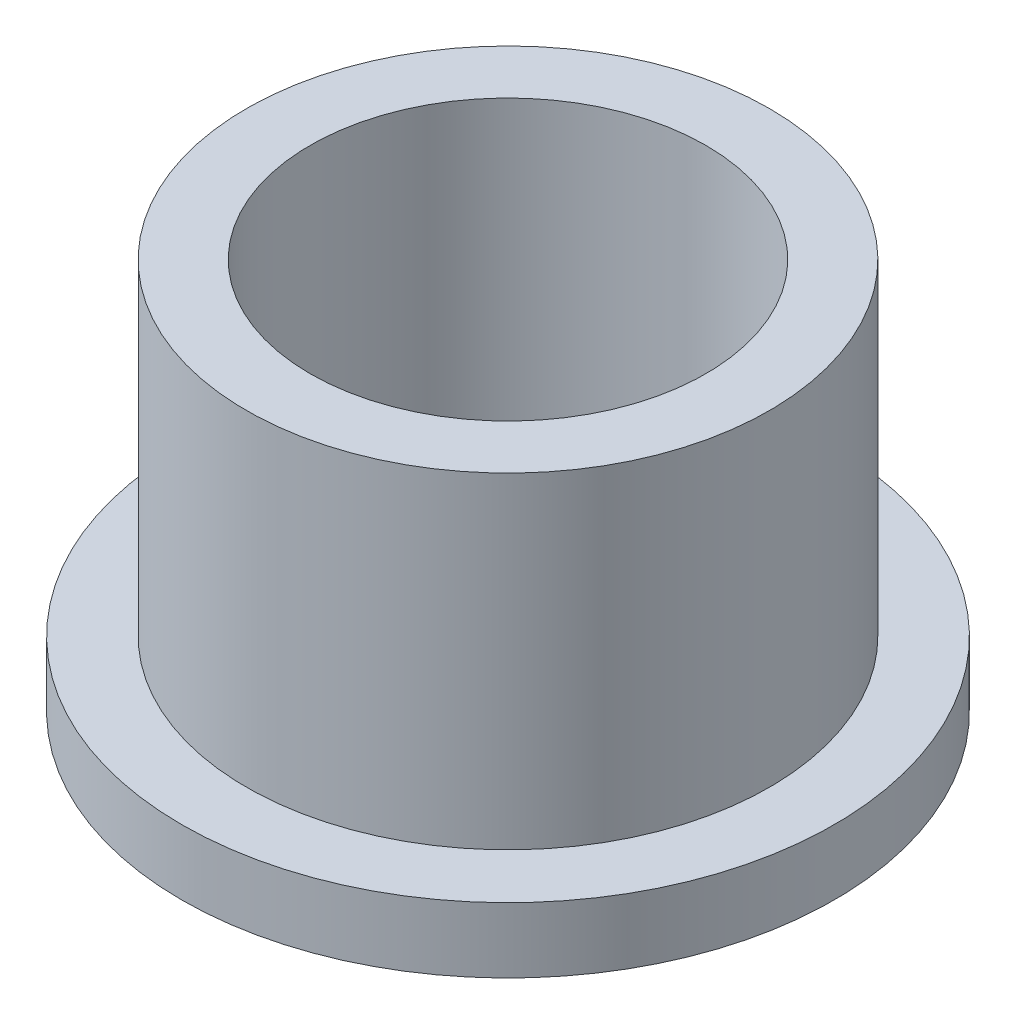
SolidWorks part; units mm, degrees
ref_plane "Front" through (0, 0, 0) normal (0, 0, 1) x (1, 0, 0)
ref_plane "Top" through (0, 0, 0) normal (0, 1, 0) x (1, 0, 0)
ref_plane "Right" through (0, 0, 0) normal (1, 0, 0) x (0, 0, -1)
sketch "Sketch1" plane through (0, 0, 0) normal (0, 1, 0) x (1, 0, 0)
  circle A0 centre (0, 0) radius 4.8133
  circle A1 centre (0, 0) radius 6.3627
  circle A2 centre (0, 0) radius 7.9375
  dimension "ID" = 9.6266
  dimension "OD" = 12.7254
  dimension "FlangeOD" = 15.875
sketch "Sketch2" plane through (0, 0, 0) normal (0, 1, 0) x (1, 0, 0)
  circle A0 centre (0, 0) radius 4.8133 construction
  circle A1 centre (0, 0) radius 6.3627 construction
  circle A2 centre (0, 0) radius 4.8133
  circle A3 centre (0, 0) radius 6.3627
extrude "Boss-Extrude1" add sketch "Sketch2" along normal blind 9.525
sketch "Sketch3" plane through (0, 0, 0) normal (0, 1, 0) x (1, 0, 0)
  circle A0 centre (0, 0) radius 7.9375 construction
  circle A1 centre (0, 0) radius 6.3627 construction
  circle A2 centre (0, 0) radius 7.9375
  circle A3 centre (0, 0) radius 6.3627
extrude "Boss-Extrude2" add sketch "Sketch3" along normal blind 1.5875
